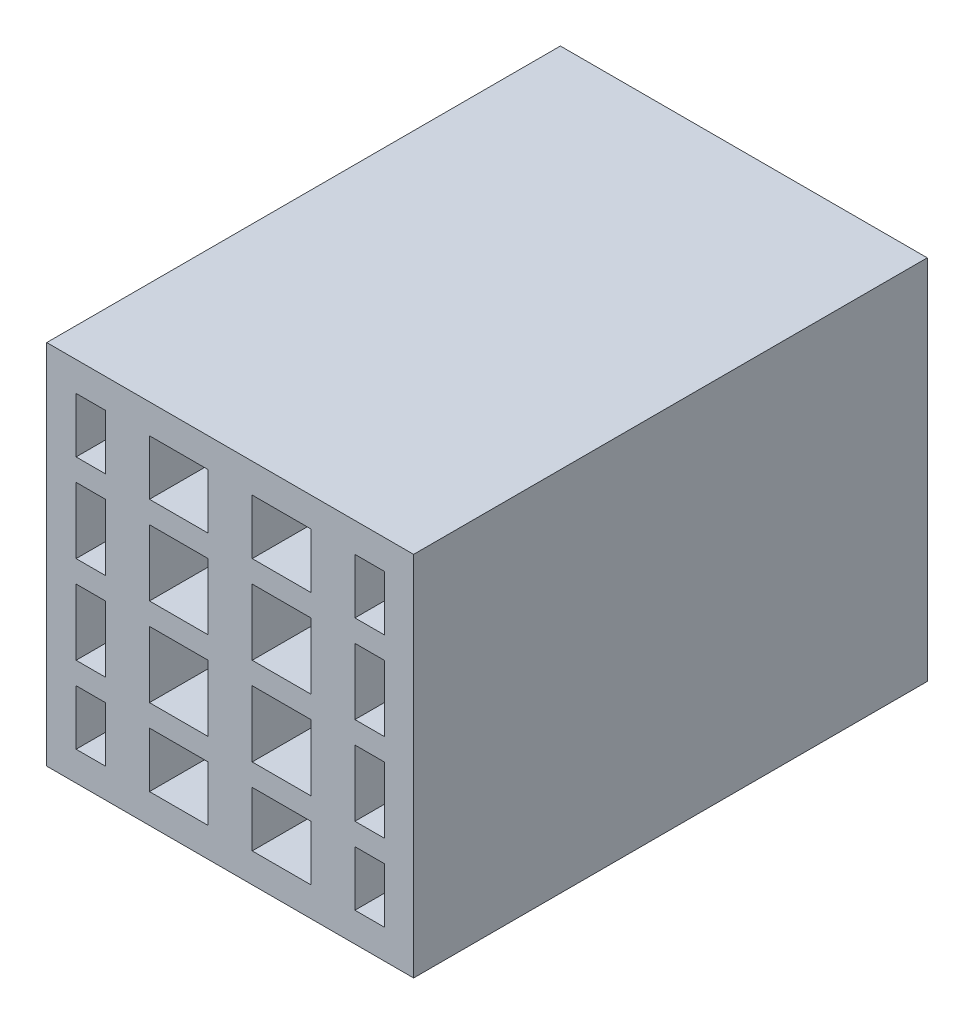
SolidWorks part; units mm, degrees
ref_plane "前视基准面" through (0, 0, 0) normal (0, 0, 1) x (1, 0, 0)
ref_plane "上视基准面" through (0, 0, 0) normal (0, 1, 0) x (1, 0, 0)
ref_plane "右视基准面" through (0, 0, 0) normal (1, 0, 0) x (0, 0, -1)
sketch "草图8" plane through (0, 0, 0) normal (0, 0, 1) x (1, 0, 0)
  line L0 (0, 7.8741) -> (0, -9.2542) construction
  line L1 (-12.5, -12.5) -> (12.5, -12.5)
  line L2 (-12.5, -12.5) -> (-12.5, 12.5)
  line L3 (-12.5, 12.5) -> (12.5, 12.5)
  line L4 (12.5, -12.5) -> (12.5, 12.5)
  line L5 (-12.5, -12.5) -> (12.5, 12.5) construction
  line L6 (-12.5, 12.5) -> (12.5, -12.5) construction
  line L7 (-16.0619, 0) -> (15.5648, 0) construction
  line L8 (-3.5, 7.8741) -> (-3.5, -9.2542) construction
  line L9 (-9.5, 7.8741) -> (-9.5, -9.2542) construction
  line L10 (5.5, 10.5) -> (1.5, 10.5)
  line L15 (-5.5, -10.5) -> (-1.5, -10.5)
  line L20 (-5.5, -10.5) -> (-5.5, 10.5)
  line L21 (-5.5, 10.5) -> (-1.5, 10.5)
  line L26 (-1.5, -10.5) -> (-1.5, 10.5)
  line L27 (-5.5, -10.5) -> (-1.5, 10.5) construction
  line L28 (-5.5, 10.5) -> (-1.5, -10.5) construction
  line L29 (-10.5, -10.5) -> (-8.5, -10.5)
  line L30 (-10.5, -10.5) -> (-10.5, 10.5)
  line L31 (-10.5, 10.5) -> (-8.5, 10.5)
  line L32 (-8.5, -10.5) -> (-8.5, 10.5)
  line L33 (-10.5, -10.5) -> (-8.5, 10.5) construction
  line L34 (-10.5, 10.5) -> (-8.5, -10.5) construction
  line L35 (1.5, -10.5) -> (1.5, 10.5)
  line L36 (5.5, -10.5) -> (1.5, -10.5)
  line L37 (5.5, -10.5) -> (5.5, 10.5)
  line L38 (10.5, 10.5) -> (8.5, 10.5)
  line L39 (8.5, -10.5) -> (8.5, 10.5)
  line L40 (10.5, -10.5) -> (8.5, -10.5)
  line L41 (10.5, -10.5) -> (10.5, 10.5)
  point P0 (0, 0)
  point P14 (-7, 0)
  point P15 (-3.5, 0)
  point P17 (-3, 0)
  point P21 (-9.5, 0)
  point P22 (-9, 0)
  dimension "D1" = 3.5
  dimension "D2" = 6
extrude "凸台-拉伸7" add sketch "草图8" along normal blind 25
sketch "草图9" plane through (0, 0, 0) normal (0, 0, -1) x (-1, 0, 0)
  line L1 (-12.5, -12.5) -> (12.5, -12.5)
  line L2 (-12.5, -12.5) -> (-12.5, 12.5)
  line L3 (-12.5, 12.5) -> (12.5, 12.5)
  line L4 (12.5, -12.5) -> (12.5, 12.5)
  line L5 (-12.5, -12.5) -> (12.5, 12.5) construction
  line L6 (-12.5, 12.5) -> (12.5, -12.5) construction
  point P0 (0, 0)
extrude "凸台-拉伸8" add sketch "草图9" along normal blind 2
sketch "草图11" plane through (0, 0, -2) normal (0, 0, -1) x (-1, 0, 0)
  line L1 (-12.5, -12.5) -> (12.5, -12.5)
  line L2 (-12.5, -12.5) -> (-12.5, 12.5)
  line L3 (-12.5, 12.5) -> (12.5, 12.5)
  line L4 (12.5, -12.5) -> (12.5, 12.5)
  line L5 (-12.5, -12.5) -> (12.5, 12.5) construction
  line L6 (-12.5, 12.5) -> (12.5, -12.5) construction
  point P0 (0, 0)
extrude "凸台-拉伸9" add sketch "草图11" along normal blind 6
sketch "草图12" plane through (0, 0, -8) normal (0, 0, -1) x (-1, 0, 0)
  line L1 (-10.5, -10.5) -> (10.5, -10.5)
  line L2 (-10.5, -10.5) -> (-10.5, 10.5)
  line L3 (-10.5, 10.5) -> (10.5, 10.5)
  line L4 (10.5, -10.5) -> (10.5, 10.5)
  line L5 (-10.5, -10.5) -> (10.5, 10.5) construction
  line L6 (-10.5, 10.5) -> (10.5, -10.5) construction
  point P0 (0, 0)
extrude "切除-拉伸1" cut sketch "草图12" against normal blind 6
sketch "草图13" plane through (0, 0, -8) normal (0, 0, -1) x (-1, 0, 0)
  line L1 (-12.5, -12.5) -> (12.5, -12.5)
  line L2 (-12.5, -12.5) -> (-12.5, 12.5)
  line L3 (-12.5, 12.5) -> (12.5, 12.5)
  line L4 (12.5, -12.5) -> (12.5, 12.5)
  line L5 (-12.5, -12.5) -> (12.5, 12.5) construction
  line L6 (-12.5, 12.5) -> (12.5, -12.5) construction
  point P0 (0, 0)
extrude "凸台-拉伸10" add sketch "草图13" along normal blind 2
sketch "草图14" plane through (0, 0, 25) normal (0, 0, 1) x (1, 0, 0)
  line L0 (-16.6961, 0) -> (20.7273, 0) construction
  line L1 (-12.5, 12.5) -> (-12.5, -12.5) construction
  line L2 (12.5, -0.75) -> (-12.5, -0.75)
  line L3 (12.5, -0.75) -> (12.5, 0.75)
  line L4 (12.5, 0.75) -> (-12.5, 0.75)
  line L5 (-12.5, -0.75) -> (-12.5, 0.75)
  line L6 (12.5, -0.75) -> (-12.5, 0.75) construction
  line L7 (12.5, 0.75) -> (-12.5, -0.75) construction
  line L12 (12.5, 5.25) -> (-12.5, 5.25)
  line L13 (12.5, 5.25) -> (12.5, 6.75)
  line L14 (12.5, 6.75) -> (-12.5, 6.75)
  line L15 (-12.5, 5.25) -> (-12.5, 6.75)
  line L16 (12.5, 5.25) -> (-12.5, 6.75) construction
  line L17 (12.5, 6.75) -> (-12.5, 5.25) construction
  line L18 (12.5, -6.75) -> (-12.5, -5.25) construction
  line L19 (12.5, -5.25) -> (-12.5, -6.75) construction
  line L20 (-12.5, -5.25) -> (-12.5, -6.75)
  line L21 (12.5, -6.75) -> (-12.5, -6.75)
  line L22 (12.5, -5.25) -> (12.5, -6.75)
  line L23 (12.5, -5.25) -> (-12.5, -5.25)
  point P3 (0, 0)
  point P11 (0, 6)
  point P19 (0, -6)
  dimension "D1" = 2
extrude "凸台-拉伸11" add sketch "草图14" against normal blind 25
sketch "草图15" plane through (0, 0, 25) normal (0, 0, 1) x (1, 0, 0)
  line L0 (-8.5, -10.5) -> (-5.5, -10.5) construction
  line L1 (-7, -10.5) -> (-7, -12.5) construction
  line L2 (-12.5, -12.5) -> (12.5, -12.5) construction
sketch "草图16" plane through (0, -12.5, 0) normal (0, -1, 0) x (1, 0, 0)
  line L0 (-7, 25) -> (-7, -10)
  line L1 (-8.5, 25) -> (-5.5, 25) construction
  line L2 (12.5, -10) -> (-12.5, -10) construction
  line L3 (-12.5, 20) -> (12.5, 20)
  line L4 (-12.5, 25) -> (-12.5, -10) construction
  line L5 (12.5, 25) -> (12.5, -10) construction
  line L6 (-12.5, 25) -> (12.5, 25) construction
  dimension "D1" = 5
sketch "草图17" plane through (0, 0, 25) normal (0, 0, 1) x (1, 0, 0)
  line L1 (-7, -12.5) -> (-7, 12.5)
  line L2 (12.5, 12.5) -> (-12.5, 12.5) construction
sketch "草图18" plane through (0, 12.5, 0) normal (0, 1, 0) x (1, 0, 0)
  line L0 (-7, -25) -> (-7, 10)
  line L1 (-12.5, -20) -> (12.5, -20)
